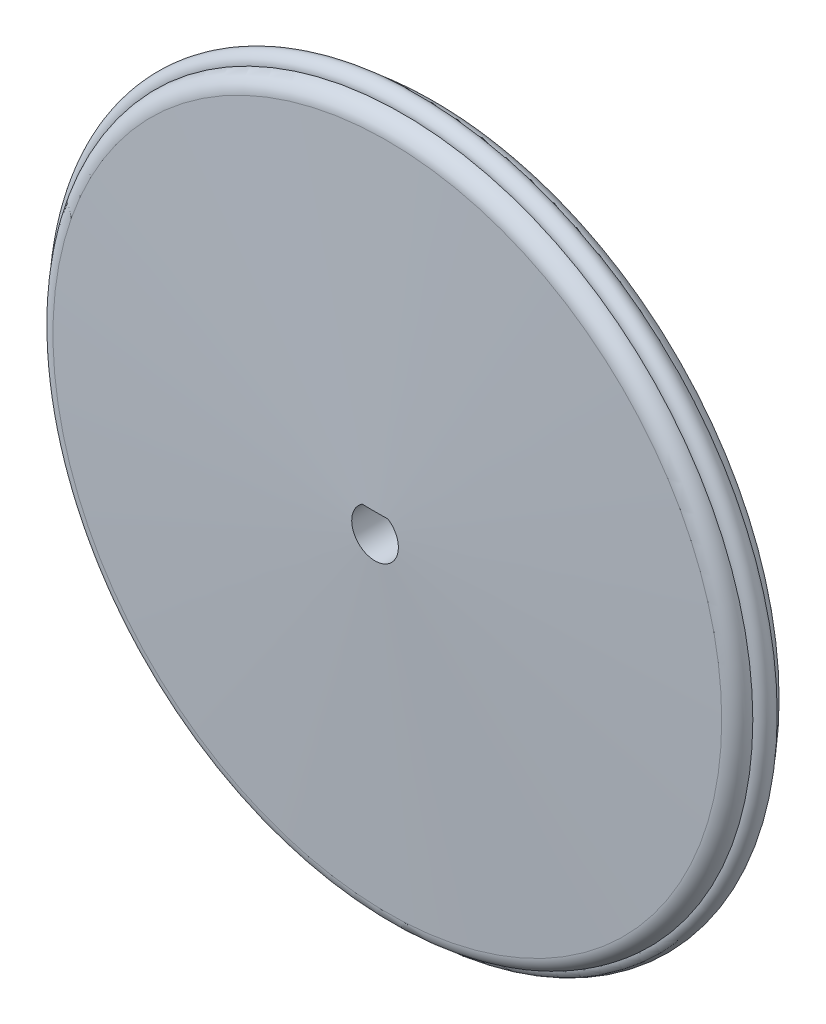
SolidWorks part; units mm, degrees
ref_plane "Plan de face" through (0, 0, 0) normal (0, 0, 1) x (1, 0, 0)
ref_plane "Plan de dessus" through (0, 0, 0) normal (0, 1, 0) x (1, 0, 0)
ref_plane "Plan de droite" through (0, 0, 0) normal (1, 0, 0) x (0, 0, -1)
sketch "Esquisse2" plane through (0, 0, 0) normal (1, 0, 0) x (0, 0, -1)
  line L0 (0, 128.7879) -> (0, -38.5432) construction
  line L1 (-77.2545, 0) -> (83.8756, 0) construction
  line L2 (5, 0) -> (-5, 0)
  line L3 (-5, 0) -> (-3.3, 43)
  line L4 (-3.3, 43) -> (-3.3, 45) construction
  line L5 (-3.3, 45) -> (-1.3, 45) construction
  line L6 (-1.3, 45) -> (-1.3, 43.7) construction
  line L7 (-1.3, 43.7) -> (0, 43.7) construction
  line L8 (-1.3, 45) -> (1.3, 45) construction
  line L9 (1.3, 43.7) -> (0, 43.7) construction
  line L10 (1.3, 45) -> (1.3, 43.7) construction
  line L11 (3.3, 45) -> (1.3, 45) construction
  line L12 (3.3, 43) -> (3.3, 45) construction
  line L13 (77.2545, 0) -> (-83.8756, 0) construction
  line L14 (5, 0) -> (3.3, 43)
  arc A0 (-3.3, 43) -> (-1.3, 45) centre (-1.2177, 42.9177) cw
  arc A1 (-1.3, 45) -> (1.3, 45) centre (0, 45) ccw
  arc A2 (3.3, 43) -> (1.3, 45) centre (1.2177, 42.9177) ccw
  point P23 (0, 0)
  dimension "D5" = 2
  dimension "D1" = 45
  dimension "D2" = 2
  dimension "D3" = 1.3
  dimension "D4" = 1.3
  dimension "D6" = 5
revolve "Révolution1" add sketch "Esquisse2" angle 360 about L1
sketch "Esquisse3" plane through (0, 0, 0) normal (0, 0, 1) x (1, 0, 0)
  line L0 (0, 0) -> (22.2154, 0) construction
  line L1 (0, 0) -> (0, 9.136) construction
  line L2 (-1.6583, 2.5) -> (1.6583, 2.5)
  arc A0 (-1.6583, 2.5) -> (1.6583, 2.5) centre (0, 0) ccw
  point P8 (0, 2.5)
  dimension "D1" = 3
  dimension "D2" = 2.5
extrude "Enlèv. mat.-Extru.3" cut sketch "Esquisse3" against normal through all both and the other way through all contours L2 A0
sketch "Esquisse4" plane through (0, 0, 0) normal (1, 0, 0) x (0, 0, -1)
  line L0 (0, 0) -> (46.0868, 0) construction
  arc A0 (-1.3, 45) -> (1.3, 45) centre (0, 45) ccw construction
  arc A1 (-1.3, 45) -> (1.3, 45) centre (0, 45) ccw
  circle A2 centre (0, 45) radius 1.3
revolve "Révolution2" add sketch "Esquisse4" angle 360 about L0
